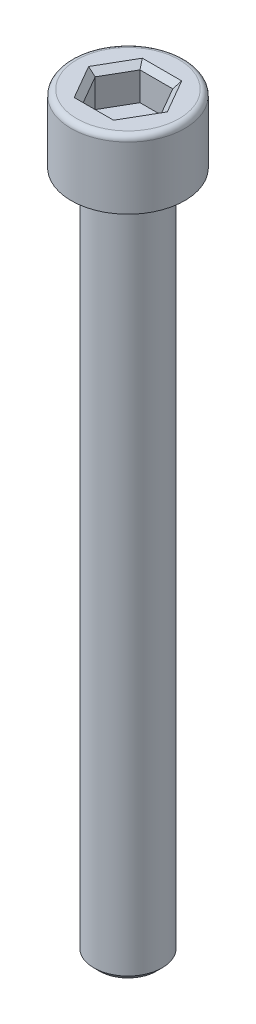
SolidWorks part; units mm, degrees
ref_plane "Plano frontal" through (0, 0, 0) normal (0, 0, 1) x (1, 0, 0)
ref_plane "Plano superior" through (0, 0, 0) normal (0, 1, 0) x (1, 0, 0)
ref_plane "Plano direito" through (0, 0, 0) normal (1, 0, 0) x (0, 0, -1)
sketch "Esboço1" plane through (0, 0, 0) normal (0, 1, 0) x (1, 0, 0)
  circle A0 centre (0, 0) radius 3
extrude "Ressalto-extrusão1" add sketch "Esboço1" against normal blind 60
sketch "Esboço2" plane through (0, 0, 0) normal (0, 1, 0) x (1, 0, 0)
  circle A0 centre (0, 0) radius 5
  dimension "D1" = 10
extrude "Ressalto-extrusão2" add sketch "Esboço2" along normal blind 6
fillet "Filete1" radius 0.5 1 edges at (0, 6, 5)
sketch "Esboço3" plane through (0, 6, 0) normal (0, 1, 0) x (1, 0, 0)
  line L1 (2.8868, 0) -> (1.4434, 2.5)
  line L2 (1.4434, 2.5) -> (-1.4434, 2.5)
  line L3 (-1.4434, 2.5) -> (-2.8868, 0)
  line L4 (-2.8868, 0) -> (-1.4434, -2.5)
  line L5 (-1.4434, -2.5) -> (1.4434, -2.5)
  line L6 (1.4434, -2.5) -> (2.8868, 0)
  circle A0 centre (0, 0) radius 2.5 construction
extrude "Corte-extrusão1" cut sketch "Esboço3" against normal blind 3
chamfer "Chanfro3" distance 0.5 angle 45 6 edges at (-2.1651, 6, 1.25) (-2.1651, 6, -1.25) (0, 6, -2.5) (2.1651, 6, -1.25) (2.1651, 6, 1.25) (0, 6, 2.5)
chamfer "Chanfro4" distance 0.5 angle 45 1 edges at (0, -60, 3)
